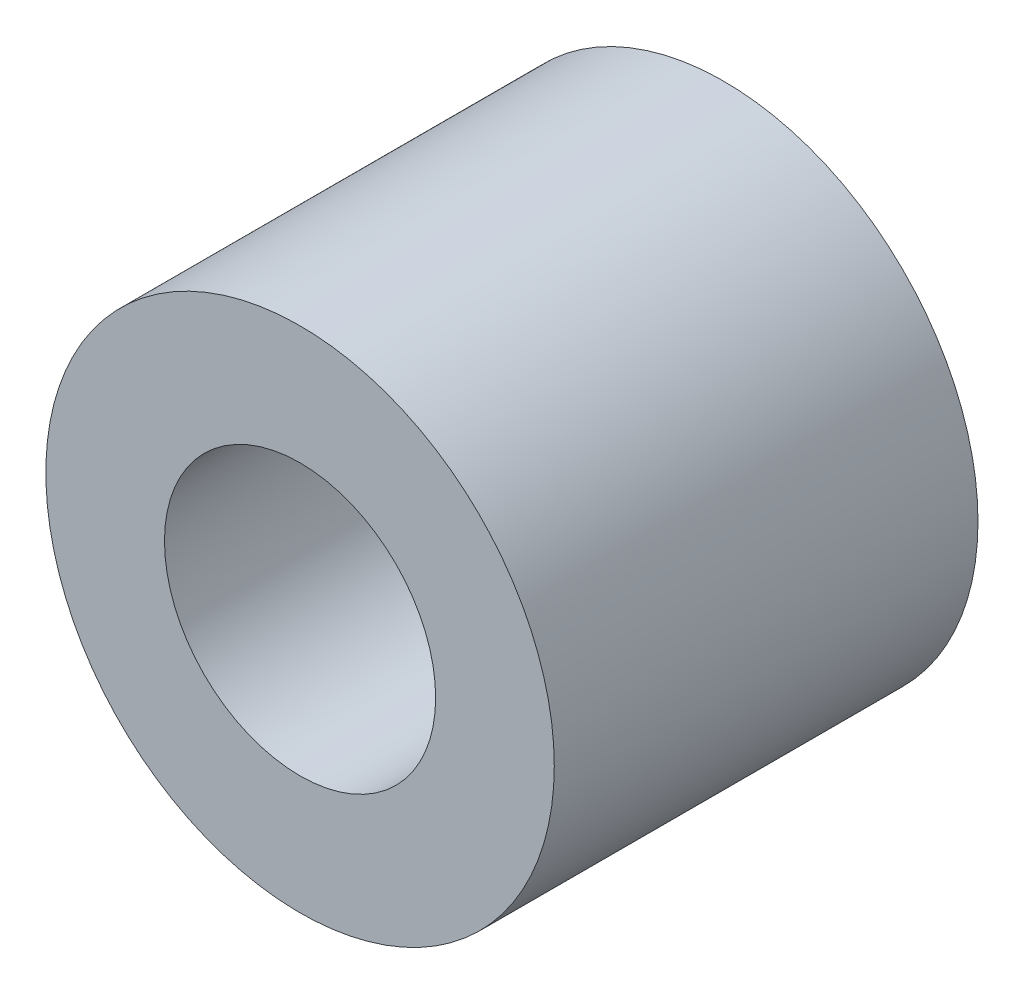
SolidWorks part; units mm, degrees
ref_plane "Front Plane" through (0, 0, 0) normal (0, 0, 1) x (1, 0, 0)
ref_plane "Top Plane" through (0, 0, 0) normal (0, 1, 0) x (1, 0, 0)
ref_plane "Right Plane" through (0, 0, 0) normal (1, 0, 0) x (0, 0, -1)
sketch "Sketch1" plane through (0, 0, 0) normal (0, 0, 1) x (1, 0, 0)
  circle A0 centre (0, 0) radius 3
  circle A1 centre (0, 0) radius 1.6
  dimension "OD" = 6
  dimension "ID" = 3.2
extrude "Extrude1" add sketch "Sketch1" along normal mid plane 5
sketch "Sketch2" plane through (0, 0, 0) normal (1, 0, 0) x (0, 0, -1)
  line L0 (-2.5, -1.6) -> (2.5, -1.6) construction
  line L3 (2.5, 1.6) -> (-2.5, 1.6) construction
  line L5 (-2.5, -1.6) -> (2.5, -1.6)
  line L6 (2.5, 1.6) -> (-2.5, 1.6)
sketch "Sketch4" plane through (0, 0, 2.5) normal (0, 0, 1) x (1, 0, 0)
  line L0 (0, 0) -> (-1.1314, 1.1314)
  line L1 (0, -1.1) -> (0, 1.1) construction
  circle A0 centre (0, 0) radius 1.6 construction
  dimension "D1" = 45
